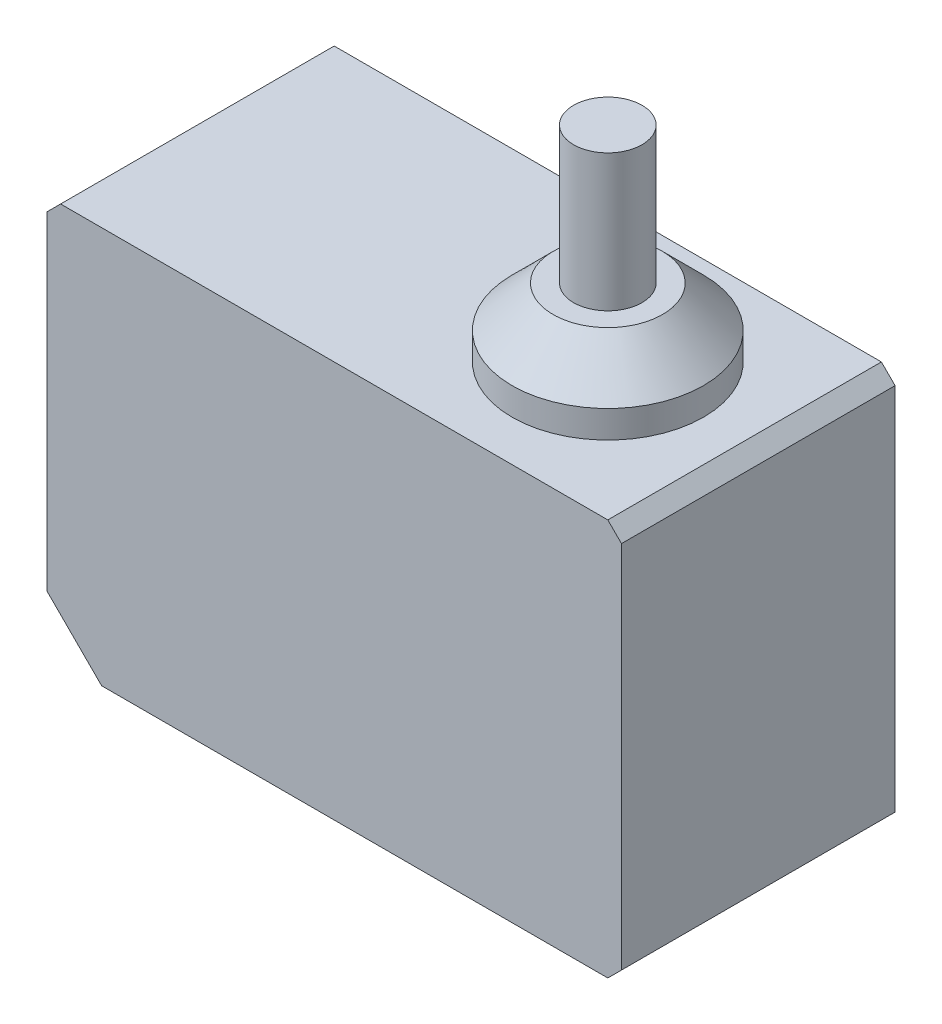
SolidWorks part; units mm, degrees
ref_plane "Front Plane" through (0, 0, 0) normal (0, 0, 1) x (1, 0, 0)
ref_plane "Top Plane" through (0, 0, 0) normal (0, 1, 0) x (1, 0, 0)
ref_plane "Right Plane" through (0, 0, 0) normal (1, 0, 0) x (0, 0, -1)
sketch "Sketch1" plane through (0, 0, 0) normal (0, 0, 1) x (1, 0, 0)
  line L1 (0, 0) -> (42, 0)
  line L2 (0, 0) -> (0, 29)
  line L3 (0, 29) -> (42, 29)
  line L4 (42, 0) -> (42, 29)
  dimension "D1" = 29
  dimension "D2" = 42
extrude "Boss-Extrude1" add sketch "Sketch1" along normal blind 20
chamfer "Chamfer1" distance 4 angle 45 1 edges at (0, 0, 10)
chamfer "Chamfer2" distance 1 angle 45 2 edges at (42, 29, 10) (0, 29, 10)
chamfer "Chamfer3" distance 1 angle 45 1 edges at (42, 0, 10)
sketch "Sketch4" plane through (0, 29, 0) normal (0, 1, 0) x (1, 0, 0)
  line L0 (1, 0) -> (1, -20) construction
  line L1 (41, -20) -> (1, -20) construction
  line L2 (1, 0) -> (1, -20) construction
  line L3 (1, -20) -> (41, -20) construction
  line L4 (41, -20) -> (41, 0) construction
  line L5 (1, -10) -> (42.1, -10) construction
  circle A0 centre (31, -10) radius 7
  dimension "D1" = 14
  dimension "D2" = 10
extrude "Boss-Extrude2" add sketch "Sketch4" along normal blind 5
chamfer "Chamfer4" distance 3 angle 45 1 edges at (31, 34, 17)
sketch "Sketch5" plane through (0, 34, 0) normal (0, 1, 0) x (1, 0, 0)
  circle A0 centre (31, -10) radius 2.5
  dimension "D1" = 5
extrude "Boss-Extrude3" add sketch "Sketch5" along normal blind 10
